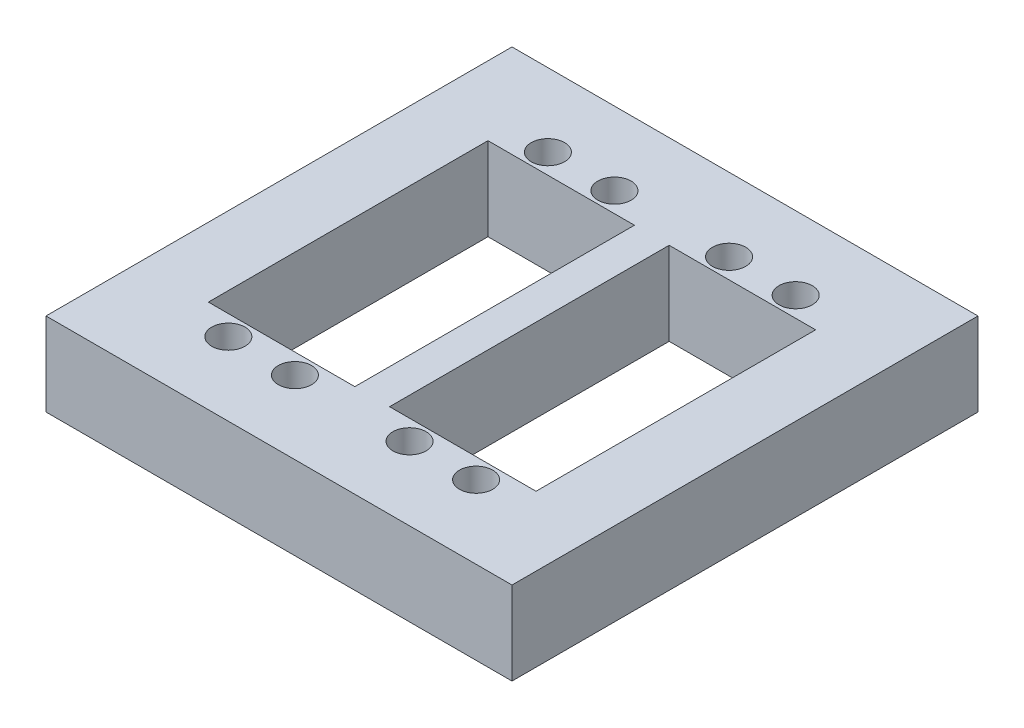
SolidWorks part; units mm, degrees
ref_plane "Front Plane" through (0, 0, 0) normal (0, 0, 1) x (1, 0, 0)
ref_plane "Top Plane" through (0, 0, 0) normal (0, 1, 0) x (1, 0, 0)
ref_plane "Right Plane" through (0, 0, 0) normal (1, 0, 0) x (0, 0, -1)
sketch "Sketch1" plane through (0, 0, 0) normal (0, 1, 0) x (1, 0, 0)
  line L0 (0, 74.7873) -> (0, -69.1899) construction
  line L1 (-35, 35) -> (35, 35)
  line L2 (-35, 35) -> (-35, -35)
  line L3 (-35, -35) -> (35, -35)
  line L4 (35, 35) -> (35, -35)
  line L5 (-35, 35) -> (35, -35) construction
  line L6 (-35, -35) -> (35, 35) construction
  line L7 (-24.6085, 21) -> (-2.6085, 21)
  line L8 (-24.6085, 21) -> (-24.6085, -21)
  line L9 (-24.6085, -21) -> (-2.6085, -21)
  line L10 (-2.6085, 21) -> (-2.6085, -21)
  line L11 (-24.6085, 21) -> (-2.6085, -21) construction
  line L12 (-24.6085, -21) -> (-2.6085, 21) construction
  line L13 (-120.0494, 0) -> (109.3545, 0) construction
  line L14 (35, 35) -> (-35, -35) construction
  line L15 (24.6085, -21) -> (2.6085, -21)
  line L16 (2.6085, 21) -> (2.6085, -21)
  line L17 (24.6085, 21) -> (2.6085, 21)
  line L18 (24.6085, 21) -> (24.6085, -21)
  circle A0 centre (-18.6085, 24) radius 2.5
  circle A1 centre (-8.6085, 24) radius 2.5
  circle A2 centre (-8.6085, -24) radius 2.5
  circle A3 centre (-18.6085, -24) radius 2.5
  circle A4 centre (8.6085, -24) radius 2.5
  circle A5 centre (18.6085, -24) radius 2.5
  circle A6 centre (8.6085, 24) radius 2.5
  circle A7 centre (18.6085, 24) radius 2.5
  point P0 (0, 0)
  point P6 (-13.6085, 0)
  dimension "D6" = 5
  dimension "D7" = 5
  dimension "D1" = 70
  dimension "D2" = 70
  dimension "D3" = 22
  dimension "D4" = 42
  dimension "D5" = 0
  dimension "D8" = 10
  dimension "D9" = 24
  dimension "D10" = 24
  dimension "D11" = 6
extrude "Boss-Extrude1" add sketch "Sketch1" along normal blind 12.5
